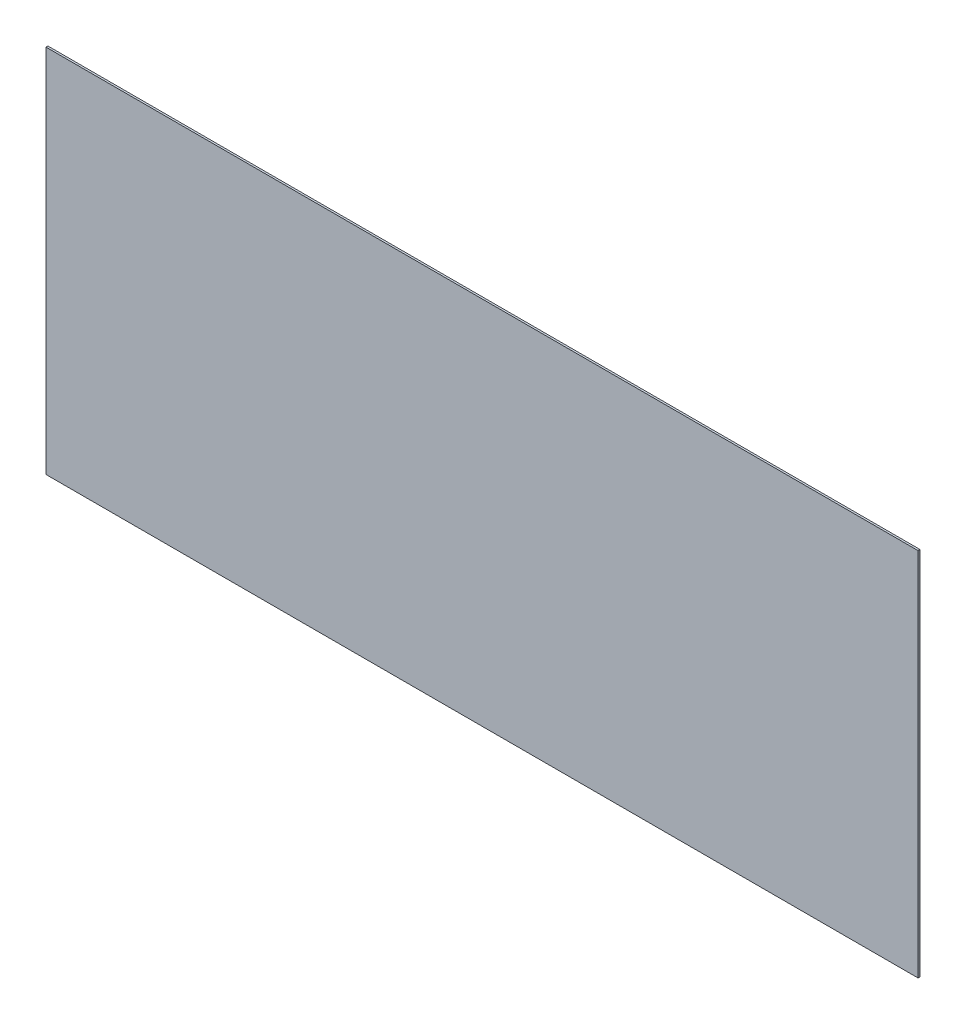
SolidWorks part; units mm, degrees
material "1345 Alloy"
ref_plane "Front Plane" through (0, 0, 0) normal (0, 0, 1) x (1, 0, 0)
ref_plane "Top Plane" through (0, 0, 0) normal (0, 1, 0) x (1, 0, 0)
ref_plane "Right Plane" through (0, 0, 0) normal (1, 0, 0) x (0, 0, -1)
sketch "Sketch1" plane through (0, 0, 0) normal (0, 0, 1) x (1, 0, 0)
  line L1 (-225, 95.5) -> (225, 95.5)
  line L2 (-225, 95.5) -> (-225, -95.5)
  line L3 (-225, -95.5) -> (225, -95.5)
  line L4 (225, 95.5) -> (225, -95.5)
  line L5 (-225, 95.5) -> (225, -95.5) construction
  line L6 (-225, -95.5) -> (225, 95.5) construction
  point P0 (0, 0)
  dimension "D1" = 450
  dimension "D2" = 191
extrude "Boss-Extrude1" add sketch "Sketch1" along normal blind 1
